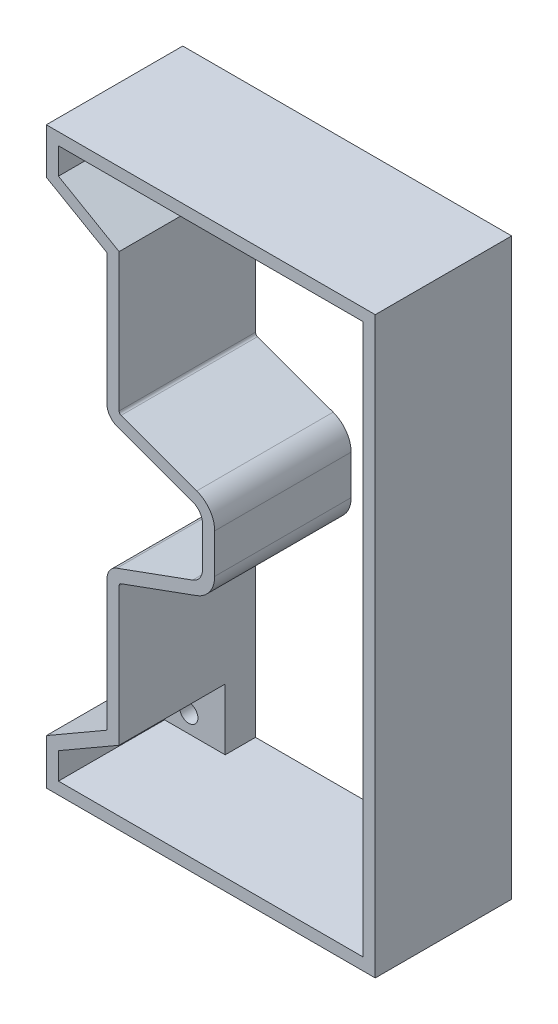
SolidWorks part; units mm, degrees
ref_plane "Спереди" through (0, 0, 0) normal (0, 0, 1) x (1, 0, 0)
ref_plane "Сверху" through (0, 0, 0) normal (0, 1, 0) x (1, 0, 0)
ref_plane "Справа" through (0, 0, 0) normal (1, 0, 0) x (0, 0, -1)
sketch "Эскиз1" plane through (0, 0, 0) normal (0, 0, 1) x (1, 0, 0)
  line L0 (4.8, -18.15) -> (15.9, -18.15)
  line L1 (20.9, -13.15) -> (20.9, 13.15)
  line L2 (15.9, 18.15) -> (4.8, 18.15)
  line L5 (4.8, 14.1025) -> (4.8, 4.996)
  line L6 (4.9316, 4.8081) -> (9.9234, 2.9912)
  line L7 (11.1078, 1.2998) -> (11.1078, -1.2998)
  line L8 (9.9234, -2.9912) -> (4.9316, -4.8081)
  line L9 (4.8, -4.996) -> (4.8, -14.1025)
  line L12 (9.6498, -2.2395) -> (4.658, -4.0564)
  line L13 (4, -4.996) -> (4, -13.6406)
  line L14 (4, -13.6406) -> (0, -15.95)
  line L15 (0, -15.95) -> (0, -18.95)
  line L16 (0, -18.95) -> (21.7, -18.95)
  line L17 (21.7, -18.95) -> (21.7, 18.95)
  line L18 (21.7, 18.95) -> (0, 18.95)
  line L19 (0, 18.95) -> (0, 15.95)
  line L20 (0, 15.95) -> (4, 13.6406)
  line L21 (4, 13.6406) -> (4, 4.996)
  line L22 (4.658, 4.0564) -> (9.6498, 2.2395)
  line L23 (10.3078, 1.2998) -> (10.3078, -1.2998)
  line L24 (9.6498, -2.2395) -> (4.658, -4.0564)
  line L25 (4, -4.996) -> (4, -13.6406)
  line L26 (4, -13.6406) -> (0, -15.95)
  line L27 (0, -15.95) -> (0, -18.95)
  line L28 (0, -18.95) -> (21.7, -18.95)
  line L29 (21.7, -18.95) -> (21.7, 18.95)
  line L30 (21.7, 18.95) -> (0, 18.95)
  line L31 (0, 18.95) -> (0, 15.95)
  line L32 (0, 15.95) -> (4, 13.6406)
  line L33 (4, 13.6406) -> (4, 4.996)
  line L34 (4.658, 4.0564) -> (9.6498, 2.2395)
  line L35 (10.3078, 1.2998) -> (10.3078, -1.2998)
  line L36 (4.8, -14.1025) -> (4.8, -18.15)
  line L37 (4.8, 14.1025) -> (4.8, 18.15)
  line L38 (15.9, -18.15) -> (20.9, -13.15)
  line L39 (0.8, -18.15) -> (20.9, -18.15) construction
  line L40 (0.8, -16.4119) -> (0.8, -18.15) construction
  line L41 (4.8, -14.1025) -> (0.8, -16.4119) construction
  line L42 (20.9, 18.15) -> (0.8, 18.15) construction
  line L43 (0.8, 18.15) -> (0.8, 16.4119) construction
  line L44 (0.8, 16.4119) -> (4.8, 14.1025) construction
  line L45 (20.9, 13.15) -> (15.9, 18.15)
  line L47 (20.9, -18.15) -> (20.9, 18.15) construction
  arc A0 (4.8, 4.996) -> (4.9316, 4.8081) centre (5, 4.996) ccw
  arc A1 (11.1078, 1.2998) -> (9.9234, 2.9912) centre (9.3078, 1.2998) ccw
  arc A2 (9.9234, -2.9912) -> (11.1078, -1.2998) centre (9.3078, -1.2998) ccw
  arc A3 (4.9316, -4.8081) -> (4.8, -4.996) centre (5, -4.996) ccw
  arc A4 (4.658, -4.0564) -> (4, -4.996) centre (5, -4.996) ccw
  arc A5 (4, 4.996) -> (4.658, 4.0564) centre (5, 4.996) ccw
  arc A6 (10.3078, 1.2998) -> (9.6498, 2.2395) centre (9.3078, 1.2998) ccw
  arc A7 (9.6498, -2.2395) -> (10.3078, -1.2998) centre (9.3078, -1.2998) ccw
  arc A8 (4.658, -4.0564) -> (4, -4.996) centre (5, -4.996) ccw
  arc A9 (4, 4.996) -> (4.658, 4.0564) centre (5, 4.996) ccw
  arc A10 (10.3078, 1.2998) -> (9.6498, 2.2395) centre (9.3078, 1.2998) ccw
  arc A11 (9.6498, -2.2395) -> (10.3078, -1.2998) centre (9.3078, -1.2998) ccw
  circle A12 centre (2.4, -16.95) radius 0.6
  circle A13 centre (2.4, 16.95) radius 0.6
  circle A14 centre (19.3, -16.95) radius 0.6
  circle A15 centre (19.3, 16.95) radius 0.6
  dimension "D3" = 1.2
  dimension "D5" = 1.2
  dimension "D12" = 1.2
  dimension "D13" = 2.4
  dimension "D17" = 1.2
  dimension "D18" = 1.2
  dimension "D4" = 1.2
  dimension "D6" = 5.8
  dimension "D7" = 5.8
  dimension "D8" = 5.8
  dimension "D9" = 5.8
  dimension "D10" = 2.4
  dimension "D11" = 2.4
  dimension "D14" = 2
  dimension "D15" = 1.2
  dimension "D16" = 2.4
  dimension "D1" = 0
  dimension "D2" = 0.8
extrude "Бобышка-Вытянуть1" add sketch "Эскиз1" along normal blind 2
sketch "Эскиз3" plane through (0, 0, 2) normal (0, 0, 1) x (1, 0, 0)
  line L0 (0.8, -18.15) -> (20.9, -18.15)
  line L1 (20.9, -18.15) -> (20.9, 18.15)
  line L2 (20.9, 18.15) -> (0.8, 18.15)
  line L3 (0.8, 18.15) -> (0.8, 16.4119)
  line L4 (0.8, 16.4119) -> (4.8, 14.1025)
  line L5 (4.8, 14.1025) -> (4.8, 4.996)
  line L6 (4.9316, 4.8081) -> (9.9234, 2.9912)
  line L7 (11.1078, 1.2998) -> (11.1078, -1.2998)
  line L8 (9.9234, -2.9912) -> (4.9316, -4.8081)
  line L9 (4.8, -4.996) -> (4.8, -14.1025)
  line L10 (4.8, -14.1025) -> (0.8, -16.4119)
  line L11 (0.8, -16.4119) -> (0.8, -18.15)
  line L12 (9.6498, -2.2395) -> (4.658, -4.0564)
  line L13 (4, -4.996) -> (4, -13.6406)
  line L14 (4, -13.6406) -> (0, -15.95)
  line L15 (0, -15.95) -> (0, -18.95)
  line L16 (0, -18.95) -> (21.7, -18.95)
  line L17 (21.7, -18.95) -> (21.7, 18.95)
  line L18 (21.7, 18.95) -> (0, 18.95)
  line L19 (0, 18.95) -> (0, 15.95)
  line L20 (0, 15.95) -> (4, 13.6406)
  line L21 (4, 13.6406) -> (4, 4.996)
  line L22 (4.658, 4.0564) -> (9.6498, 2.2395)
  line L23 (10.3078, 1.2998) -> (10.3078, -1.2998)
  line L24 (9.6498, -2.2395) -> (4.658, -4.0564)
  line L25 (4, -4.996) -> (4, -13.6406)
  line L26 (4, -13.6406) -> (0, -15.95)
  line L27 (0, -15.95) -> (0, -18.95)
  line L28 (0, -18.95) -> (21.7, -18.95)
  line L29 (21.7, -18.95) -> (21.7, 18.95)
  line L30 (21.7, 18.95) -> (0, 18.95)
  line L31 (0, 18.95) -> (0, 15.95)
  line L32 (0, 15.95) -> (4, 13.6406)
  line L33 (4, 13.6406) -> (4, 4.996)
  line L34 (4.658, 4.0564) -> (9.6498, 2.2395)
  line L35 (10.3078, 1.2998) -> (10.3078, -1.2998)
  arc A0 (4.8, 4.996) -> (4.9316, 4.8081) centre (5, 4.996) ccw
  arc A1 (11.1078, 1.2998) -> (9.9234, 2.9912) centre (9.3078, 1.2998) ccw
  arc A2 (9.9234, -2.9912) -> (11.1078, -1.2998) centre (9.3078, -1.2998) ccw
  arc A3 (4.9316, -4.8081) -> (4.8, -4.996) centre (5, -4.996) ccw
  arc A4 (9.6498, -2.2395) -> (10.3078, -1.2998) centre (9.3078, -1.2998) ccw
  arc A5 (4.658, -4.0564) -> (4, -4.996) centre (5, -4.996) ccw
  arc A6 (4, 4.996) -> (4.658, 4.0564) centre (5, 4.996) ccw
  arc A7 (10.3078, 1.2998) -> (9.6498, 2.2395) centre (9.3078, 1.2998) ccw
  arc A8 (9.6498, -2.2395) -> (10.3078, -1.2998) centre (9.3078, -1.2998) ccw
  arc A9 (4.658, -4.0564) -> (4, -4.996) centre (5, -4.996) ccw
  arc A10 (4, 4.996) -> (4.658, 4.0564) centre (5, 4.996) ccw
  arc A11 (10.3078, 1.2998) -> (9.6498, 2.2395) centre (9.3078, 1.2998) ccw
  dimension "D1" = 0
  dimension "D2" = 0.8
extrude "Бобышка-Вытянуть2" add sketch "Эскиз3" along normal blind 7
